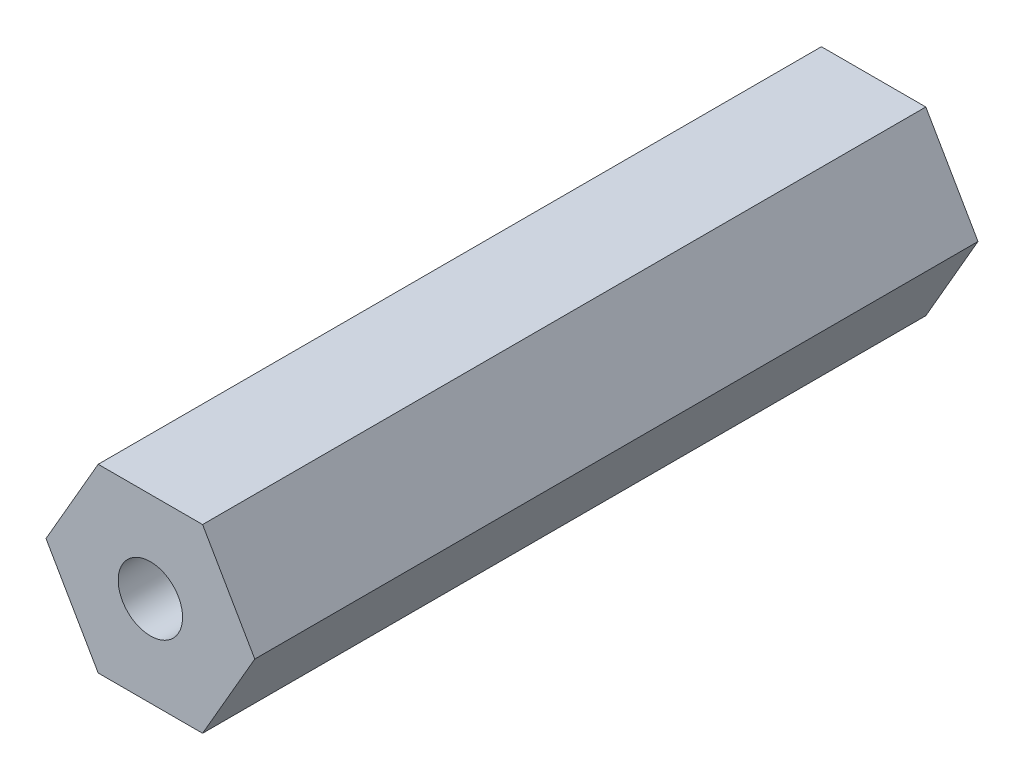
SolidWorks part; units mm, degrees
material "6061 Alloy"
ref_plane "Front Plane" through (0, 0, 0) normal (0, 0, 1) x (1, 0, 0)
ref_plane "Top Plane" through (0, 0, 0) normal (0, 1, 0) x (1, 0, 0)
ref_plane "Right Plane" through (0, 0, 0) normal (1, 0, 0) x (0, 0, -1)
sketch "Sketch2" plane through (0, 0, 0) normal (0, 0, 1) x (1, 0, 0)
  line L0 (-1.8331, 3.175) -> (1.8331, 3.175)
  line L1 (1.8331, 3.175) -> (3.6662, 0)
  line L2 (3.6662, 0) -> (1.8331, -3.175)
  line L3 (1.8331, -3.175) -> (-1.8331, -3.175)
  line L4 (-1.8331, -3.175) -> (-3.6662, 0)
  line L5 (-3.6662, 0) -> (-1.8331, 3.175)
  dimension "D1" = 3.175
extrude "Extrude1" add sketch "Sketch2" against normal blind 25.4
hole_wizard "#4-40 Tapped Hole1" positions "Sketch4" profile "Sketch3" tap size "#4-40" standard "Ansi Inch"
sketch "Sketch4" plane through (0, 0, 0) normal (0, 0, 1) x (1, 0, 0)
  point P0 (0, 0)
sketch "Sketch3" plane through (0, 0, 0) normal (1, 0, 0) x (0, -1, 0)
  line L0 (0, 0) -> (0, 8.2738)
  line L1 (0, 8.2738) -> (1.1303, 7.5946)
  line L2 (1.1303, 7.5946) -> (1.1303, 0)
  line L5 (1.1303, 0) -> (0, 0)
  line L10 (0, 8.2738) -> (-1.1303, 7.5946) construction
  line L11 (0, -6.35) -> (0, 107.95) construction
  dimension "Tap Drill Dia." = 2.2606
  dimension "Tap Drill Depth" = 7.5946
  dimension "Drill Angle" = 118
cosmetic thread "Hole Thread1" parameters "D1"=5.6896, "D2"=2.8448
hole_wizard "#4-40 Tapped Hole2" positions "Sketch6" profile "Sketch5" tap size "#4-40" standard "Ansi Inch"
sketch "Sketch6" plane through (0, 0, -25.4) normal (0, 0, -1) x (-1, 0, 0)
  point P0 (0, 0)
sketch "Sketch5" plane through (0, 0, -25.4) normal (1, 0, 0) x (0, 1, 0)
  line L0 (0, 0) -> (0, 8.2738)
  line L1 (0, 8.2738) -> (1.1303, 7.5946)
  line L2 (1.1303, 7.5946) -> (1.1303, 0)
  line L5 (1.1303, 0) -> (0, 0)
  line L10 (0, 8.2738) -> (-1.1303, 7.5946) construction
  line L11 (0, -6.35) -> (0, 107.95) construction
  dimension "Tap Drill Dia." = 2.2606
  dimension "Tap Drill Depth" = 7.5946
  dimension "Drill Angle" = 118
cosmetic thread "Hole Thread2" parameters "D1"=5.6896, "D2"=2.8448
